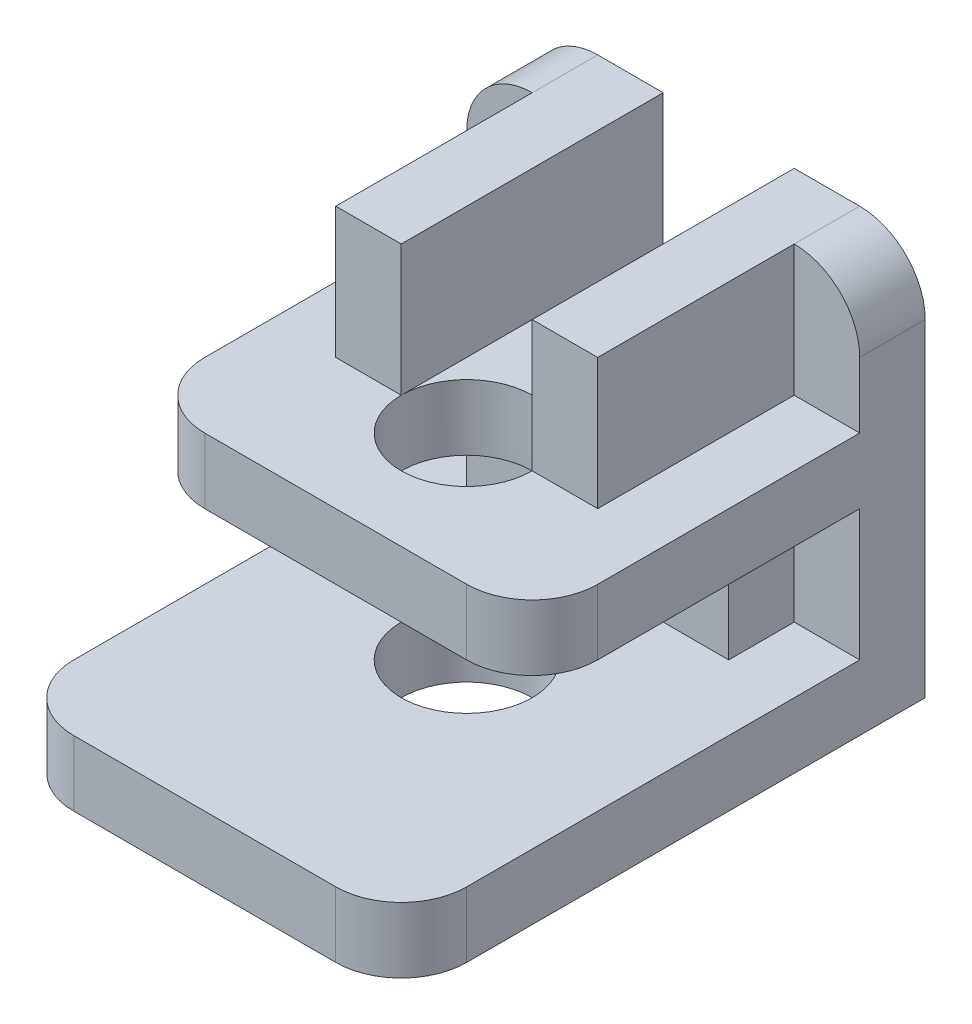
SolidWorks part; units mm, degrees
ref_plane "정면" through (0, 0, 0) normal (0, 0, 1) x (1, 0, 0)
ref_plane "윗면" through (0, 0, 0) normal (0, 1, 0) x (1, 0, 0)
ref_plane "우측면" through (0, 0, 0) normal (1, 0, 0) x (0, 0, -1)
sketch "스케치1" plane through (0, 0, 0) normal (0, 1, 0) x (1, 0, 0)
  line L1 (0, 0) -> (60, 0)
  line L2 (0, 0) -> (0, 80)
  line L3 (0, 80) -> (60, 80)
  line L4 (60, 0) -> (60, 80)
  dimension "D1" = 80
  dimension "D2" = 60
extrude "보스-돌출1" add sketch "스케치1" along normal blind 10
sketch "스케치2" plane through (0, 10, 0) normal (0, 1, 0) x (1, 0, 0)
  line L0 (60, 0) -> (60, 80) construction
  line L1 (0, 80) -> (60, 80)
  line L2 (0, 80) -> (0, 70)
  line L3 (0, 70) -> (60, 70)
  line L4 (60, 80) -> (60, 70)
  dimension "D1" = 10
extrude "보스-돌출2" add sketch "스케치2" along normal blind 50
sketch "스케치3" plane through (0, 0, -70) normal (0, 0, 1) x (1, 0, 0)
  line L0 (0, 60) -> (0, 10) construction
  line L1 (0, 40) -> (60, 40)
  line L2 (0, 40) -> (0, 30)
  line L3 (0, 30) -> (60, 30)
  line L4 (60, 40) -> (60, 30)
  line L5 (60, 60) -> (60, 10) construction
  line L6 (0, 0) -> (60, 0) construction
  dimension "D1" = 10
  dimension "D2" = 30
extrude "보스-돌출3" add sketch "스케치3" along normal blind 50
sketch "스케치4" plane through (0, 0, -70) normal (0, 0, 1) x (1, 0, 0)
  line L0 (0, 30) -> (60, 30) construction
  line L1 (10, 30) -> (50, 30)
  line L2 (10, 30) -> (10, 10)
  line L3 (10, 10) -> (50, 10)
  line L4 (50, 30) -> (50, 10)
  line L5 (0, 10) -> (60, 10) construction
  line L6 (0, 30) -> (0, 10) construction
  line L7 (60, 30) -> (60, 10) construction
  dimension "D1" = 10
  dimension "D2" = 10
extrude "보스-돌출4" add sketch "스케치4" along normal blind 10
sketch "스케치5" plane through (0, 0, -70) normal (0, 0, 1) x (1, 0, 0)
  line L0 (0, 60) -> (60, 60) construction
  line L1 (10, 60) -> (50, 60)
  line L2 (10, 60) -> (10, 40)
  line L3 (10, 40) -> (50, 40)
  line L4 (50, 60) -> (50, 40)
  line L5 (60, 40) -> (0, 40) construction
  line L7 (10, 30) -> (10, 10) construction
  line L9 (50, 10) -> (50, 30) construction
extrude "보스-돌출5" add sketch "스케치5" along normal blind 30
sketch "스케치6" plane through (0, 0, -40) normal (0, 0, 1) x (1, 0, 0)
  line L0 (50, 60) -> (10, 60) construction
  line L1 (20, 60) -> (40, 60)
  line L2 (20, 60) -> (20, 40)
  line L3 (20, 40) -> (40, 40)
  line L4 (40, 60) -> (40, 40)
  line L5 (10, 40) -> (50, 40) construction
  line L6 (10, 60) -> (10, 40) construction
  dimension "D1" = 20
  dimension "D2" = 10
extrude "컷-돌출1" cut sketch "스케치6" against normal blind 50
fillet "필렛1" radius 10 8 edges at (0, 60, -75) (5, 60, -70) (60, 60, -75) (0, 35, -20) (60, 35, -20) (55, 60, -70) (60, 5, 0) (0, 5, 0)
sketch "스케치7" plane through (0, 10, 0) normal (0, 1, 0) x (1, 0, 0)
  line L0 (60, 80) -> (0, 80) construction
  line L1 (60, 10) -> (60, 70) construction
  circle A0 centre (30, 40) radius 10
  dimension "D1" = 20
  dimension "D2" = 40
  dimension "D3" = 30
extrude "컷-돌출2" cut sketch "스케치7" against normal blind 50 and the other way blind 50
